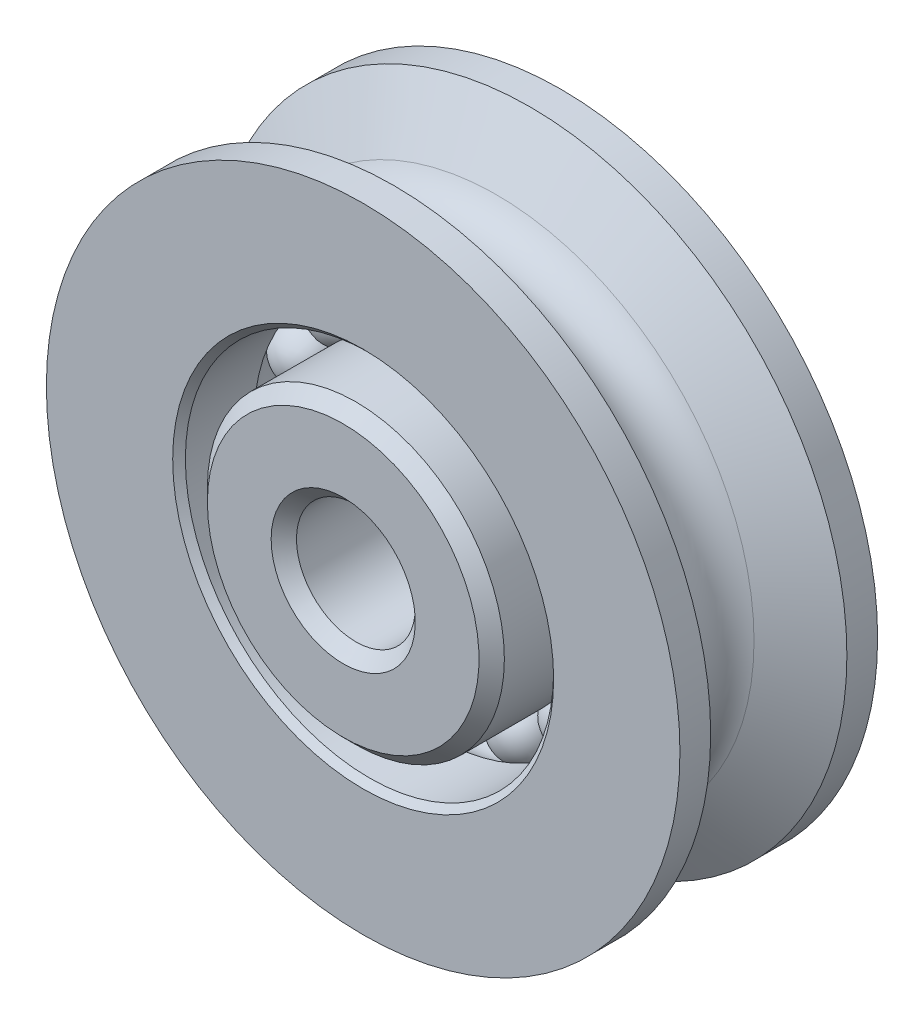
SolidWorks part; units mm, degrees
ref_plane "Front" through (0, 0, 0) normal (0, 0, 1) x (1, 0, 0)
ref_plane "Top" through (0, 0, 0) normal (0, 1, 0) x (1, 0, 0)
ref_plane "Right" through (0, 0, 0) normal (1, 0, 0) x (0, 0, -1)
sketch "Sketch1" plane through (0, 0, 0) normal (1, 0, 0) x (0, 0, -1)
  line L0 (2.7305, 12.7) -> (3.9624, 12.7)
  line L1 (-2.7305, 12.7) -> (-3.9624, 12.7)
  line L2 (-2.7305, 12.7) -> (-1.3796, 10.3271)
  line L3 (0.9525, 7.3819) -> (3.9624, 7.3819)
  line L4 (4.7625, 2.3812) -> (-4.7625, 2.3812)
  line L5 (-0.9525, 5.9531) -> (-4.7625, 5.9531)
  line L6 (2.7305, 12.7) -> (1.3796, 10.3271)
  line L8 (-4.7625, 0) -> (4.7625, 0) construction
  line L10 (3.9624, 12.7) -> (3.9624, 7.3819)
  line L13 (-4.7625, 5.9531) -> (-4.7625, 2.3812)
  line L14 (0, 9.525) -> (0, -9.525) construction
  line L16 (4.7625, 5.9531) -> (4.7625, 2.3812)
  line L17 (-3.9624, 12.7) -> (-3.9624, -12.7) construction
  line L18 (-3.9624, 7.3819) -> (-0.9525, 7.3819)
  line L20 (4.7625, 5.9531) -> (0.9525, 5.9531)
  line L21 (-3.9624, 7.3819) -> (-3.9624, 12.7)
  arc A0 (-1.3796, 10.3271) -> (1.3796, 10.3271) centre (0, 11.1125) ccw
  circle A1 centre (0, 11.1125) radius 1.5875 construction
  circle A2 centre (0, 0) radius 2.3813 construction
  circle A3 centre (0, 0) radius 5.9531 construction
  arc A4 (-0.9525, 5.9531) -> (0.9525, 5.9531) centre (0, 6.6675) ccw
  circle A5 centre (0, -11.1125) radius 1.5875 construction
  arc A6 (0.9525, 7.3819) -> (-0.9525, 7.3819) centre (0, 6.6675) ccw
  point P28 (-3.9624, 0)
  dimension "Rope Dia" = 3.175
  dimension "D1" = 11.9063
  dimension "Shaft Dia" = 4.7625
  dimension "D3" = 1.4288
  dimension "D2" = 2.3813
  dimension "Wd" = 9.525
  dimension "D8" = 1.2319
  dimension "Groove Dia" = 19.05
  dimension "OD" = 25.4
  dimension "w Wd" = 7.9248
revolve "Revolve1" add sketch "Sketch1" angle 360 about L8
sketch "Sketch2" plane through (0, 0, 0) normal (1, 0, 0) x (0, 0, -1)
  line L0 (0, 9.525) -> (0, -9.525) construction
  line L1 (0, 7.8581) -> (0, 5.4769)
  arc A0 (0.9525, 7.3819) -> (-0.9525, 7.3819) centre (0, 6.6675) ccw construction
  arc A1 (0, 5.4769) -> (0, 7.8581) centre (0, 6.6675) ccw
revolve "Revolve2" add sketch "Sketch2" angle 360 about L1
pattern_circular "CirPattern1" count 16 over 360 about axis through (0, 0, 0) along (0, 0, 1) of bodies 117
chamfer "Chamfer1" distance 0.508 angle 45 4 edges at (2.3812, 0, -4.7625) (5.9531, 0, -4.7625) (5.9531, 0, 4.7625) (2.3812, 0, 4.7625)
chamfer "Chamfer2" distance 0.254 angle 45 2 edges at (7.3819, 0, -3.9624) (7.3819, 0, 3.9624)
equation "\"D1@Sketch1\" = \"Shaft Dia@Sketch1\" * 2.5"
equation "\"D2@Sketch1\" = \"Rope Dia@Sketch1\" * .75"
equation "\"D3@Sketch1\" = \"D2@Sketch1\" * .6"
